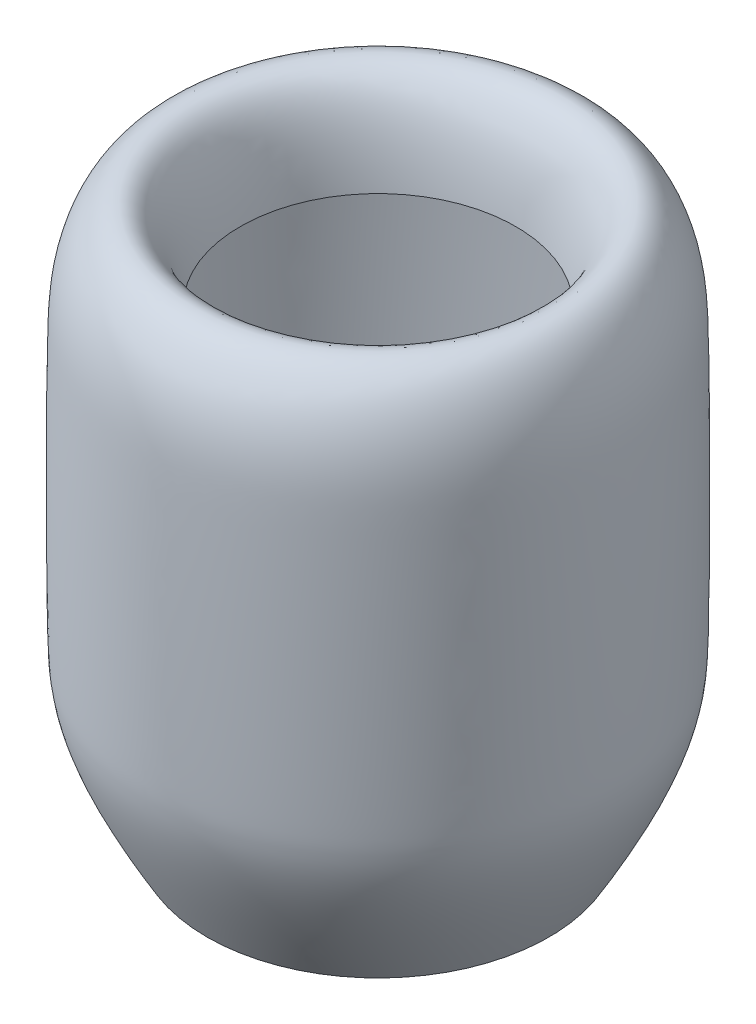
SolidWorks part; units mm, degrees
ref_plane "Front Plane" through (0, 0, 0) normal (0, 0, 1) x (1, 0, 0)
ref_plane "Top Plane" through (0, 0, 0) normal (0, 1, 0) x (1, 0, 0)
ref_plane "Right Plane" through (0, 0, 0) normal (1, 0, 0) x (0, 0, -1)
sketch "Sketch1" plane through (0, 0, 0) normal (0, 0, 1) x (1, 0, 0)
  line L0 (0, 0) -> (0, -225302.2188) construction
  line L1 (0, 0) -> (225302.2188, 0) construction
  line L2 (75, 358.9047) -> (75, -132.8896) construction
  line L3 (46, 279.115) -> (46, -70.3173) construction
  line L4 (-111.8818, -100) -> (191.8765, -100) construction
  line L5 (55, -60.3178) -> (55, -166.6222) construction
  line L6 (102.8246, -150) -> (32.2822, -150) construction
  line L7 (55, -150) -> (55.864, -150.5035)
  line L8 (45.0065, 0.1142) -> (46, 0)
  spline S0 degree 3 poles (46, 0) (50.9934, 43.4224) (74.4192, 29.0667) (75.8876, -30.1707) (75.6135, -93.03) (74.5222, -105.8967) (71.8537, -121.0755) (55, -150) knots 0 0 0 0 0.332423 0.386421 0.677937 0.742939 1 1 1 1
  spline S1 degree 1 poles (45.0065, 0.1142) (55.864, -150.5035) knots 0 0 1 1 construction
  spline S2 degree 3 poles (45.0065, 0.1142) (45.0648, 0.621) (45.1885, 1.6445) (45.4495, 3.6045) (45.8071, 5.9513) (46.2822, 8.5873) (46.9746, 11.8728) (47.9449, 15.5561) (49.2608, 19.3274) (50.7143, 22.4792) (52.8225, 25.8907) (55.7624, 28.7524) (59.7756, 29.9447) (63.7354, 28.856) (67.2723, 25.9932) (70.384, 21.6592) (72.9687, 16.0495) (74.9082, 9.3544) (76.0065, 1.7819) (76.3111, -6.5013) (76.4455, -15.8213) (76.5597, -26.0723) (76.6241, -36.8501) (76.6595, -51.4726) (76.6213, -65.7623) (76.5233, -78.3122) (76.4228, -86.504) (76.3193, -92.0173) (76.226, -95.4747) (76.127, -98.2132) (75.9803, -100.5168) (75.7264, -102.8046) (75.3257, -105.6918) (74.6213, -109.202) (73.4736, -113.4667) (71.7395, -118.5978) (69.6871, -123.6985) (67.6093, -128.3355) (65.8149, -132.1071) (63.7667, -136.1877) (61.833, -139.8595) (60.1418, -142.966) (58.7967, -145.3862) (57.3821, -147.8825) (56.3674, -149.6395) (55.864, -150.5035) knots 0 0 0 0 0.003906 0.007812 0.015625 0.023438 0.03125 0.046875 0.0625 0.078125 0.09375 0.125 0.15625 0.1875 0.21875 0.25 0.28125 0.3125 0.34375 0.375 0.40625 0.4375 0.46875 0.5 0.5625 0.59375 0.625 0.65625 0.671875 0.6875 0.71875 0.75 0.78125 0.8125 0.84375 0.875 0.90625 0.921875 0.9375 0.953125 0.96875 0.976562 0.984375 0.992188 1 1 1 1
  dimension "D1" = 75
  dimension "D2" = 46
  dimension "D3" = 100
  dimension "D4" = 150
  dimension "D5" = 55
  dimension "D6" = 1
revolve "Revolve1" add sketch "Sketch1" angle 360 about L0
sketch "Sketch2" plane through (0, 0, 0) normal (0, 0, 1) x (1, 0, 0)
  line L0 (-131.0148, -10) -> (151.3168, -10)
  line L1 (-131.0148, -10) -> (-131.0148, 125.8036)
  line L2 (-131.0148, 125.8036) -> (151.3168, 125.8036)
  line L3 (151.3168, 125.8036) -> (151.3168, -10)
  dimension "D1" = 10
